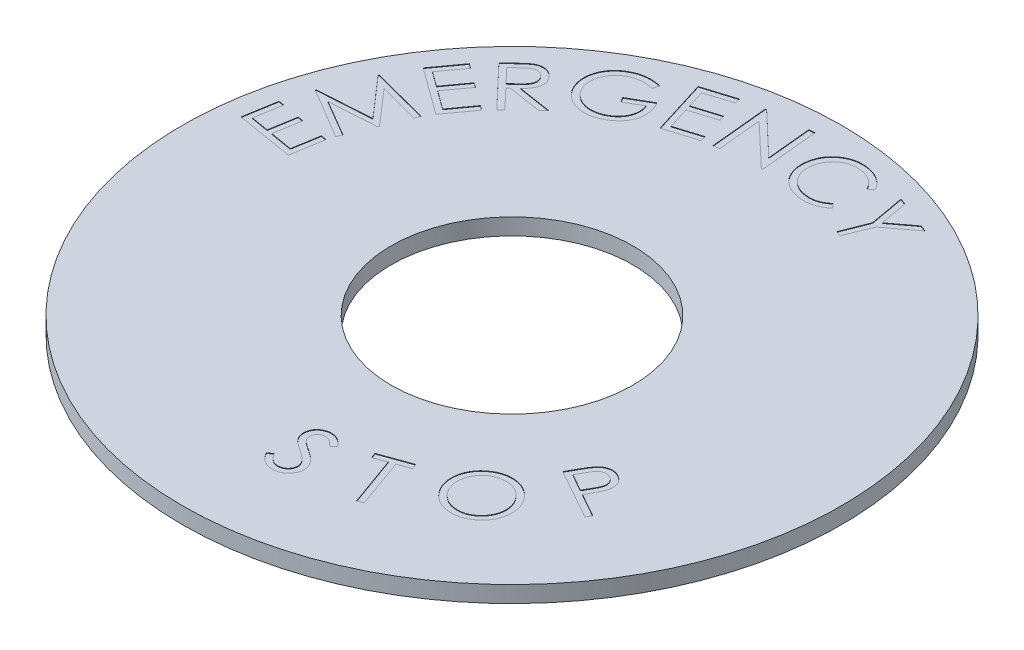
SolidWorks part; units mm, degrees
ref_plane "Front Plane" through (0, 0, 0) normal (0, 0, 1) x (1, 0, 0)
ref_plane "Top Plane" through (0, 0, 0) normal (0, 1, 0) x (1, 0, 0)
ref_plane "Right Plane" through (0, 0, 0) normal (1, 0, 0) x (0, 0, -1)
sketch "Sketch1" plane through (0, 0, 0) normal (0, 1, 0) x (1, 0, 0)
  circle A0 centre (0, 0) radius 30
  circle A1 centre (0, 0) radius 11
extrude "Boss-Extrude1" add sketch "Sketch1" along normal blind 1.5
sketch "Sketch2" plane through (0, 1.5, 0) normal (0, 1, 0) x (1, 0, 0)
  text T0 "                        EMERGENCY" font "Century Gothic" height in points 20
  text T1 "                   STOP" font "Century Gothic" height in points 20
extrude "Cut-Extrude1" cut sketch "Sketch2" against normal blind 0.05
